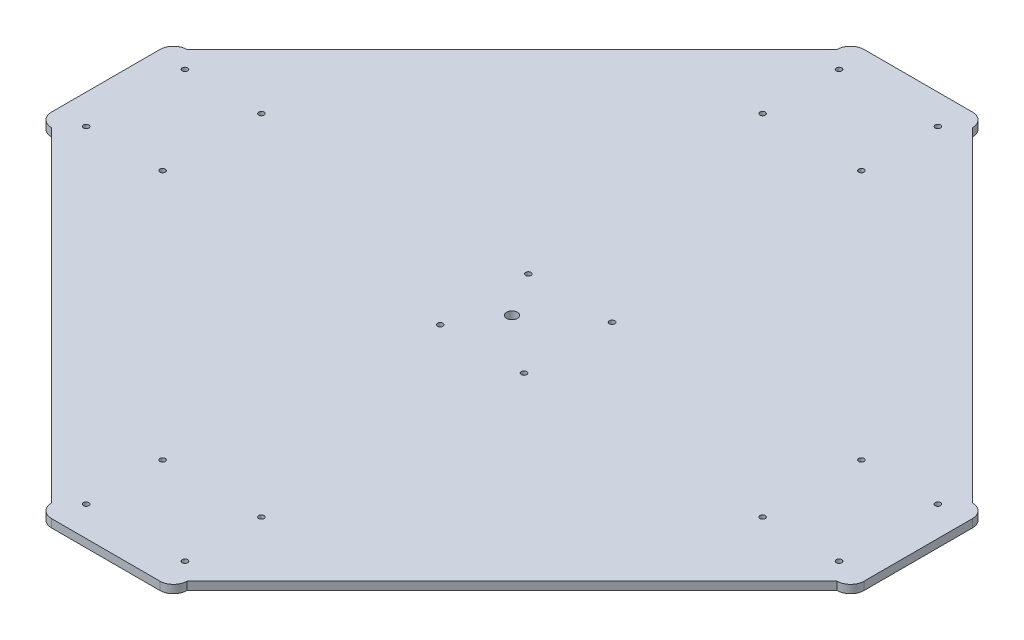
SolidWorks part; units mm, degrees
material "Acrylic (Medium-high impact)"
ref_plane "Front" through (0, 0, 0) normal (0, 0, 1) x (1, 0, 0)
ref_plane "Top" through (0, 0, 0) normal (0, 1, 0) x (1, 0, 0)
ref_plane "Right" through (0, 0, 0) normal (1, 0, 0) x (0, 0, -1)
sketch "Sketch1" plane through (0, 0, 0) normal (0, 1, 0) x (1, 0, 0)
  line L0 (-110, 50) -> (-300, 50)
  line L1 (280, -50) -> (90, -50)
  line L2 (290, -40) -> (290, 40)
  line L3 (280, 50) -> (90, 50)
  line L4 (-310, -40) -> (-310, 40)
  line L5 (-60, 100) -> (-110, 50)
  line L6 (90, 50) -> (40, 100)
  line L7 (30, -300) -> (-50, -300)
  line L8 (40, -290) -> (40, -100)
  line L9 (30, 300) -> (-50, 300)
  line L10 (-60, -290) -> (-60, -100)
  line L11 (90, -50) -> (40, -100)
  line L12 (-60, -100) -> (-110, -50)
  line L16 (-110, -50) -> (-300, -50)
  line L18 (40, 100) -> (40, 290)
  line L19 (-60, 100) -> (-60, 290)
  arc A0 (-50, 300) -> (-60, 290) centre (-50, 290) ccw
  arc A1 (40, 290) -> (30, 300) centre (30, 290) ccw
  arc A2 (290, 40) -> (280, 50) centre (280, 40) ccw
  arc A3 (280, -50) -> (290, -40) centre (280, -40) ccw
  arc A4 (30, -300) -> (40, -290) centre (30, -290) ccw
  arc A5 (-50, -300) -> (-60, -290) centre (-50, -290) cw
  arc A6 (-300, -50) -> (-310, -40) centre (-300, -40) cw
  arc A7 (-300, 50) -> (-310, 40) centre (-300, 40) ccw
  point P0 (0, 0)
  point P1 (8.4315, 46.1032)
  point P2 (128.4315, 46.1032)
  point P3 (8.4315, -56.5685)
  point P4 (128.4315, -56.5685)
  point P5 (0, 0)
  point P10 (0, 0)
  point P15 (-60, -50)
  point P17 (-60, 50)
  point P18 (-56.5685, -56.5685)
  point P23 (56.5685, 56.5685)
  point P25 (40, -50)
  point P28 (40, 50)
  point P31 (-60, 300)
  point P34 (40, 300)
  point P37 (290, 50)
  point P43 (40, -300)
  point P48 (-310, -50)
  point P51 (-310, 50)
  dimension "D1" = 600
  dimension "D5" = 10
  dimension "D2" = 100
  dimension "D3" = 100
  dimension "D4" = 600
  dimension "D6" = 190
  dimension "D7" = 190
  dimension "D8" = 190
  dimension "D9" = 190
extrude "Boss-Extrude1" add sketch "Sketch1" along normal blind 6
sketch "Sketch4" plane through (0, 6, 0) normal (0, 1, 0) x (1, 0, 0)
  line L0 (-10, 300) -> (-10, -432.1332) construction
  line L1 (30, 300) -> (-50, 300) construction
  line L2 (-338.2481, 0) -> (378.576, 0) construction
  circle A0 centre (-10, 0) radius 0.4957
extrude "Cut-Extrude3" cut sketch "Sketch4" against normal blind 10
sketch "Sketch5" plane through (0, 6, 0) normal (0, 1, 0) x (1, 0, 0)
  line L0 (-300, 50) -> (-60, 290)
  line L1 (-250, 50) -> (-60, 240)
  line L2 (-110, 50) -> (-300, 50) construction
  line L3 (-60, 100) -> (-60, 290) construction
  line L4 (-60, 240) -> (-60, 290)
  line L5 (-250, 50) -> (-300, 50)
  line L6 (40, 290) -> (280, 50)
  line L7 (280, 50) -> (230, 50)
  line L8 (230, 50) -> (40, 240)
  line L9 (40, 240) -> (40, 290)
  line L10 (280, -50) -> (40, -290)
  line L11 (40, -290) -> (40, -240)
  line L12 (40, -240) -> (230, -49.078)
  line L13 (230, -49.078) -> (280, -50)
  line L14 (-300, -50) -> (-60, -290)
  line L15 (-60, -290) -> (-60, -240)
  line L16 (-60, -240) -> (-250, -50)
  line L17 (-250, -50) -> (-300, -50)
  point P25 (-10, 2)
  dimension "D1" = 50
  dimension "D2" = 50
  dimension "D3" = 50
  dimension "D4" = 50
  dimension "D5" = 50
  dimension "D6" = 50
  dimension "D7" = 50
  dimension "D8" = 50
extrude "Boss-Extrude3" add sketch "Sketch5" against normal blind 6
sketch "Sketch6" plane through (0, 6, 0) normal (0, 1, 0) x (1, 0, 0)
  circle A0 centre (-37.8241, 287.837) radius 2
  circle A1 centre (-37.8241, 272.837) radius 2
  circle A4 centre (-46.4831, 221.5369) radius 2
  circle A5 centre (-46.4831, 135.0679) radius 2
  circle A6 centre (-69.8176, 73.3345) radius 2
  circle A7 centre (49.8176, 73.3345) radius 2
  circle A8 centre (26.4831, 135.0679) radius 2
  circle A9 centre (26.4831, 221.5369) radius 2
  circle A10 centre (191.3604, 113.6396) radius 2
  circle A11 centre (128.6396, 176.3604) radius 2
  circle A12 centre (17.8241, 272.837) radius 2
  circle A13 centre (17.8241, 287.837) radius 2
  circle A14 centre (-10, 0) radius 4
  dimension "D1" = 4
  dimension "D2" = 4
  dimension "D4" = 8
  dimension "D8" = 4
  dimension "D9" = 4
  dimension "D10" = 4
  dimension "D3" = 15
extrude "Cut-Extrude4" cut sketch "Sketch6" against normal blind 12
pattern_circular "CirPattern1" count 4 over 360 about axis through (-10, 0, 0) along (0, 1, 0) of "Cut-Extrude4"
sketch "Sketch7" plane through (0, 6, 0) normal (0, 1, 0) x (1, 0, 0)
  line L0 (40, 240) -> (230, 50) construction
  line L1 (40, 100) -> (40, 240) construction
  line L2 (90, 50) -> (40, 100) construction
  line L3 (230, 50) -> (90, 50) construction
  line L4 (90, -50) -> (229.0824, -50) construction
  line L5 (229.0824, -50) -> (40, -240) construction
  line L6 (40, -100) -> (90, -50) construction
  line L7 (40, -240) -> (40, -100) construction
  line L8 (-60, 240) -> (-60, 100) construction
  line L9 (-250, 50) -> (-60, 240) construction
  line L10 (-60, 100) -> (-110, 50) construction
  line L11 (-110, 50) -> (-250, 50) construction
  line L12 (-110, -50) -> (-60, -100) construction
  line L13 (-250, -50) -> (-110, -50) construction
  line L14 (-60, -240) -> (-250, -50) construction
  line L15 (-60, -100) -> (-60, -240) construction
  line L16 (40, 240) -> (230, 50)
  line L17 (40, 100) -> (40, 240)
  line L18 (90, 50) -> (40, 100)
  line L19 (230, 50) -> (90, 50)
  line L20 (90, -50) -> (229.0824, -50)
  line L21 (229.0824, -50) -> (40, -240)
  line L22 (40, -100) -> (90, -50)
  line L23 (40, -240) -> (40, -100)
  line L24 (-60, 240) -> (-60, 100)
  line L25 (-250, 50) -> (-60, 240)
  line L26 (-60, 100) -> (-110, 50)
  line L27 (-110, 50) -> (-250, 50)
  line L28 (-110, -50) -> (-60, -100)
  line L29 (-250, -50) -> (-110, -50)
  line L30 (-60, -240) -> (-250, -50)
  line L31 (-60, -100) -> (-60, -240)
extrude "Boss-Extrude4" add sketch "Sketch7" against normal up to surface (6 mm away) up to face at (63.3345, 0, -57.8176)
sketch "Sketch8" plane through (0, 0, 0) normal (0, -1, 0) x (-1, 0, 0)
  circle A0 centre (-279, 20) radius 2.5
  circle A1 centre (-279, -20) radius 2.5
extrude "Cut-Extrude5" [suppressed] cut sketch "Sketch8" against normal blind 144
pattern_circular "CirPattern2" [suppressed] count 4 over 360
sketch "Sketch9" plane through (0, 0, 0) normal (0, -1, 0) x (-1, 0, 0)
  circle A0 centre (-255, -20) radius 2.5
  circle A1 centre (-255, 20) radius 2.5
extrude "Cut-Extrude6" [suppressed] cut sketch "Sketch9" against normal blind 144
pattern_circular "CirPattern3" [suppressed] count 4 over 360
sketch "Sketch10" plane through (0, 6, 0) normal (0, 1, 0) x (1, 0, 0)
  line L0 (-310, 40) -> (-310, -40) construction
  line L1 (-50, -300) -> (30, -300) construction
  point P0 (-57, 33)
  point P1 (37, 33)
  point P2 (-57, -33)
  point P3 (37, -33)
  dimension "D1" = 94
  dimension "D2" = 66
  dimension "D3" = 253
  dimension "D4" = 267
ref_plane "Plane1" through (-10, 0, 0) normal (1, 0, 0) x (0, 0, -1)
ref_plane "Plane2" through (0, 0, 0) normal (0, 0, 1) x (1, 0, 0)
ref_plane "Plane3" through (-10, 0, 0) normal (-1, 0, 0) x (0, 0, 1)
sketch "Sketch11" plane through (0, 6, 0) normal (0, 1, 0) x (1, 0, 0)
  point P0 (32.7129, 23.7813)
  point P1 (-226.182, -59.3281)
  point P3 (-30.4306, -32.5)
  point P4 (31.3831, -32.5)
  point P6 (-29.1008, 23.7813)
sketch "Sketch23" plane through (0, 0, 0) normal (0, -1, 0) x (1, 0, 0)
  point P0 (-10, -24.0416)
  point P1 (-34.0416, 0)
  point P2 (-10, 24.0416)
  point P3 (14.0416, 0)
hole_wizard "Ø4.0mm Dowel Hole3" [suppressed] positions "Sketch26" profile "Sketch27" hole size "Ø4.0" standard "ANSI Metric"
sketch "Sketch26" plane through (0, 4, 0) normal (0, 1, 0) x (1, 0, 0)
  point P0 (-10, 24.0416)
  point P2 (-34.0416, 0)
  point P4 (14.0416, 0)
  point P6 (-10, -24.0416)
sketch "Sketch27" plane through (-10, 4, -24.0416) normal (1, 0, 0) x (0, 0, 1)
  line L0 (0, 0) -> (0, 99.5117)
  line L1 (0, 99.5117) -> (2, 98.31)
  line L2 (2, 98.31) -> (2, 0)
  line L5 (2, 0) -> (0, 0)
  line L10 (0, 99.5117) -> (-2, 98.31) construction
  line L11 (0, -6.35) -> (0, 107.95) construction
  dimension "Hole Dia." = 4
  dimension "Hole Depth" = 98.31
  dimension "Drill Angle" = 118
ref_plane "Plane4" through (-10, 0, 0) normal (-1, 0, 0) x (0, 0, 1)
sketch "Sketch28" plane through (0, 0, 0) normal (0, -1, 0) x (1, 0, 0)
  point P0 (-288, 36.4831)
  point P1 (-288, -36.4831)
  point P2 (-46.4831, -278)
  point P3 (26.4831, -278)
  point P4 (268, -36.4831)
  point P5 (268, 36.4831)
  point P6 (-46.4831, 278)
  point P7 (26.4831, 278)
hole_wizard "Ø4.0mm Dowel Hole4" positions "Sketch29" profile "Sketch30" hole size "Ø4.0" standard "ANSI Metric"
sketch "Sketch29" plane through (0, 0, 0) normal (0, -1, 0) x (-1, 0, 0)
  point P0 (46.4831, -278)
  point P3 (-26.4831, -278)
  point P6 (-268, -36.4831)
  point P9 (-268, 36.4831)
  point P12 (-26.4831, 278)
  point P15 (46.4831, 278)
  point P18 (288, 36.4831)
  point P21 (288, -36.4831)
sketch "Sketch30" plane through (-46.4831, 0, 278) normal (1, 0, 0) x (0, 0, -1)
  line L0 (0, 0) -> (0, 99.5117)
  line L1 (0, 99.5117) -> (2, 98.31)
  line L2 (2, 98.31) -> (2, 0)
  line L5 (2, 0) -> (0, 0)
  line L10 (0, 99.5117) -> (-2, 98.31) construction
  line L11 (0, -6.35) -> (0, 107.95) construction
  dimension "Hole Dia." = 4
  dimension "Hole Depth" = 98.31
  dimension "Drill Angle" = 118
ref_plane "Plane5" through (-10, 0, 0) normal (1, 0, 0) x (0, 0, -1)
sketch "Sketch31" plane through (0, 6, 0) normal (0, 1, 0) x (1, 0, 0)
  point P0 (31.3831, -32.5)
  point P1 (-30.4306, -32.5)
  point P2 (-30.4306, 32.5)
  point P3 (31.3831, 32.5)
hole_wizard "Ø4.0mm Dowel Hole5" positions "Sketch32" profile "Sketch33" hole size "Ø4.0" standard "ANSI Metric"
sketch "Sketch32" plane through (0, 6, 0) normal (0, 1, 0) x (1, 0, 0)
  point P0 (-30.4306, -32.5)
  point P3 (31.3831, -32.5)
  point P6 (31.3831, 32.5)
  point P9 (-30.4306, 32.5)
sketch "Sketch33" plane through (-30.4306, 6, 32.5) normal (1, 0, 0) x (0, 0, 1)
  line L0 (0, 0) -> (0, 99.5117)
  line L1 (0, 99.5117) -> (2, 98.31)
  line L2 (2, 98.31) -> (2, 0)
  line L5 (2, 0) -> (0, 0)
  line L10 (0, 99.5117) -> (-2, 98.31) construction
  line L11 (0, -6.35) -> (0, 107.95) construction
  dimension "Hole Dia." = 4
  dimension "Hole Depth" = 98.31
  dimension "Drill Angle" = 118
sketch "Sketch34" plane through (0, 6, 0) normal (0, 1, 0) x (1, 0, 0)
  line L1 (-96.5079, 83.8385) -> (-61.0984, 83.8385)
  line L2 (-96.5079, 83.8385) -> (-96.5079, 53.6534)
  line L3 (-96.5079, 53.6534) -> (-61.0984, 53.6534)
  line L4 (-61.0984, 83.8385) -> (-61.0984, 53.6534)
  line L5 (-162.6829, 53.6534) -> (-126.1125, 53.6534)
  line L6 (-162.6829, 53.6534) -> (-162.6829, -57.7993)
  line L7 (-162.6829, -57.7993) -> (-126.1125, -57.7993)
  line L8 (-126.1125, 53.6534) -> (-126.1125, -57.7993)
  line L9 (-90.703, -49.0921) -> (-61.0984, -49.0921)
  line L10 (-90.703, -49.0921) -> (-90.703, -82.1796)
  line L11 (-90.703, -82.1796) -> (-61.0984, -82.1796)
  line L12 (-61.0984, -49.0921) -> (-61.0984, -82.1796)
  line L13 (40.4861, -49.0921) -> (73.5736, -49.0921)
  line L14 (40.4861, -49.0921) -> (40.4861, -82.1796)
  line L15 (40.4861, -82.1796) -> (73.5736, -82.1796)
  line L16 (73.5736, -49.0921) -> (73.5736, -82.1796)
  line L17 (46.2909, 78.6141) -> (73.5736, 78.6141)
  line L18 (46.2909, 78.6141) -> (46.2909, 53.6534)
  line L19 (46.2909, 53.6534) -> (73.5736, 53.6534)
  line L20 (73.5736, 78.6141) -> (73.5736, 53.6534)
  line L21 (117.1098, 47.8486) -> (137.4267, 47.8486)
  line L22 (117.1098, 47.8486) -> (117.1098, -44.4482)
  line L23 (117.1098, -44.4482) -> (137.4267, -44.4482)
  line L24 (137.4267, 47.8486) -> (137.4267, -44.4482)
  line L25 (-274.7161, 19.9854) -> (-302.5792, 19.9854)
  line L26 (-274.7161, 19.9854) -> (-274.7161, 31.595)
  line L27 (-274.7161, 31.595) -> (-302.5792, 31.595)
  line L28 (-302.5792, 19.9854) -> (-302.5792, 31.595)
  line L29 (-302.5792, -19.1122) -> (-278.5542, -19.1122)
  line L30 (-302.5792, -19.1122) -> (-302.5792, -32.3742)
  line L31 (-302.5792, -32.3742) -> (-278.5542, -32.3742)
  line L32 (-278.5542, -19.1122) -> (-278.5542, -32.3742)
  line L33 (-220.4547, -106.4123) -> (-195.1978, -106.4123)
  line L34 (-220.4547, -106.4123) -> (-220.4547, -120.9836)
  line L35 (-220.4547, -120.9836) -> (-195.1978, -120.9836)
  line L36 (-195.1978, -106.4123) -> (-195.1978, -120.9836)
  line L37 (-162.6829, -167.6118) -> (-135.9411, -167.6118)
  line L38 (-162.6829, -167.6118) -> (-162.6829, -181.2117)
  line L39 (-162.6829, -181.2117) -> (-135.9411, -181.2117)
  line L40 (-135.9411, -167.6118) -> (-135.9411, -181.2117)
  line L41 (-34.2882, -266.8566) -> (-41.1209, -266.8566)
  line L42 (-34.2882, -266.8566) -> (-34.2882, -293.428)
  line L43 (-34.2882, -293.428) -> (-41.1209, -293.428)
  line L44 (-41.1209, -266.8566) -> (-41.1209, -293.428)
  line L45 (9.7444, -263.8198) -> (23.4097, -263.8198)
  line L46 (9.7444, -263.8198) -> (9.7444, -293.428)
  line L47 (9.7444, -293.428) -> (23.4097, -293.428)
  line L48 (23.4097, -263.8198) -> (23.4097, -293.428)
  line L49 (-71.0568, -113.6979) -> (40.4861, -113.6979)
  line L50 (-71.0568, -113.6979) -> (-71.0568, -162.0549)
  line L51 (-71.0568, -162.0549) -> (40.4861, -162.0549)
  line L52 (40.4861, -113.6979) -> (40.4861, -162.0549)
  line L53 (95.69, -174.4118) -> (110.29, -174.4118)
  line L54 (95.69, -174.4118) -> (95.69, -209.6969)
  line L55 (95.69, -209.6969) -> (110.29, -209.6969)
  line L56 (110.29, -174.4118) -> (110.29, -209.6969)
  line L57 (152.553, -120.9836) -> (171.7635, -120.9836)
  line L58 (152.553, -120.9836) -> (152.553, -147.4549)
  line L59 (152.553, -147.4549) -> (171.7635, -147.4549)
  line L60 (171.7635, -120.9836) -> (171.7635, -147.4549)
  line L61 (-61.0984, 154.5634) -> (40.4861, 154.5634)
  line L62 (-61.0984, 154.5634) -> (-61.0984, 122.6719)
  line L63 (-61.0984, 122.6719) -> (40.4861, 122.6719)
  line L64 (40.4861, 154.5634) -> (40.4861, 122.6719)
  line L65 (-29.0125, 262.4944) -> (-41.1209, 262.4944)
  line L66 (-29.0125, 262.4944) -> (-29.0125, 291.5133)
  line L67 (-29.0125, 291.5133) -> (-41.1209, 291.5133)
  line L68 (-41.1209, 262.4944) -> (-41.1209, 291.5133)
  line L69 (22.0893, 268.3647) -> (13.108, 268.3647)
  line L70 (22.0893, 268.3647) -> (22.0893, 292.5821)
  line L71 (22.0893, 292.5821) -> (13.108, 292.5821)
  line L72 (13.108, 268.3647) -> (13.108, 292.5821)
  line L73 (-166.1106, 142.6815) -> (-195.1978, 142.6815)
  line L74 (-166.1106, 142.6815) -> (-166.1106, 126.3185)
  line L75 (-166.1106, 126.3185) -> (-195.1978, 126.3185)
  line L76 (-195.1978, 142.6815) -> (-195.1978, 126.3185)
  line L77 (-108.4506, 208.1333) -> (-126.1125, 208.1333)
  line L78 (-108.4506, 208.1333) -> (-108.4506, 185.9264)
  line L79 (-108.4506, 185.9264) -> (-126.1125, 185.9264)
  line L80 (-126.1125, 208.1333) -> (-126.1125, 185.9264)
  line L81 (284.0075, 19.9854) -> (258.1356, 19.9854)
  line L82 (284.0075, 19.9854) -> (284.0075, 31.595)
  line L83 (284.0075, 31.595) -> (258.1356, 31.595)
  line L84 (258.1356, 19.9854) -> (258.1356, 31.595)
  line L85 (281.9279, -32.3742) -> (258.1356, -32.3742)
  line L86 (281.9279, -32.3742) -> (281.9279, -22.8342)
  line L87 (281.9279, -22.8342) -> (258.1356, -22.8342)
  line L88 (258.1356, -32.3742) -> (258.1356, -22.8342)
  line L89 (137.4267, 164.3305) -> (117.1098, 164.3305)
  line L90 (137.4267, 164.3305) -> (137.4267, 179.9641)
  line L91 (137.4267, 179.9641) -> (117.1098, 179.9641)
  line L92 (117.1098, 164.3305) -> (117.1098, 179.9641)
  line L93 (181.823, 122.6719) -> (194.1393, 122.6719)
  line L94 (181.823, 122.6719) -> (181.823, 103.4339)
  line L95 (181.823, 103.4339) -> (194.1393, 103.4339)
  line L96 (194.1393, 122.6719) -> (194.1393, 103.4339)
extrude "Boss-Extrude5" add sketch "Sketch34" against normal up to vertex (6 mm away)
